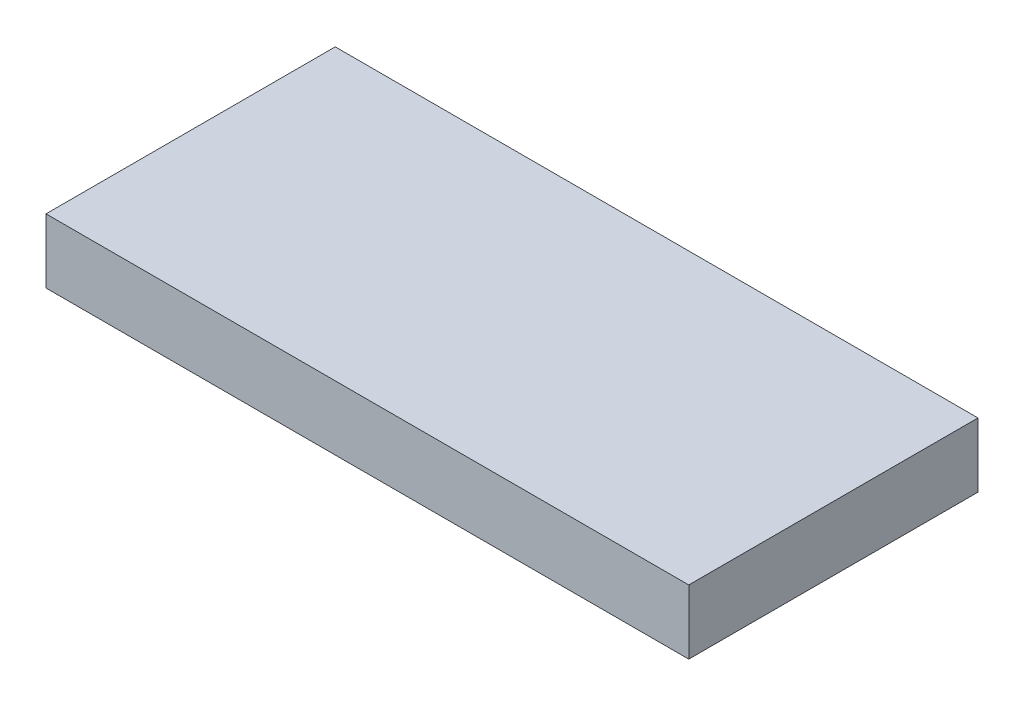
SolidWorks part; units mm, degrees
ref_plane "Front Plane" through (0, 0, 0) normal (0, 0, 1) x (1, 0, 0)
ref_plane "Top Plane" through (0, 0, 0) normal (0, 1, 0) x (1, 0, 0)
ref_plane "Right Plane" through (0, 0, 0) normal (1, 0, 0) x (0, 0, -1)
sketch "Sketch1" plane through (0, 0, 0) normal (0, 1, 0) x (1, 0, 0)
  line L1 (0, 0) -> (50.8, 0)
  line L2 (0, 0) -> (0, 22.86)
  line L3 (0, 22.86) -> (50.8, 22.86)
  line L4 (50.8, 0) -> (50.8, 22.86)
  dimension "D1" = 50.8
  dimension "D2" = 22.86
extrude "Boss-Extrude1" add sketch "Sketch1" along normal blind 5.08
